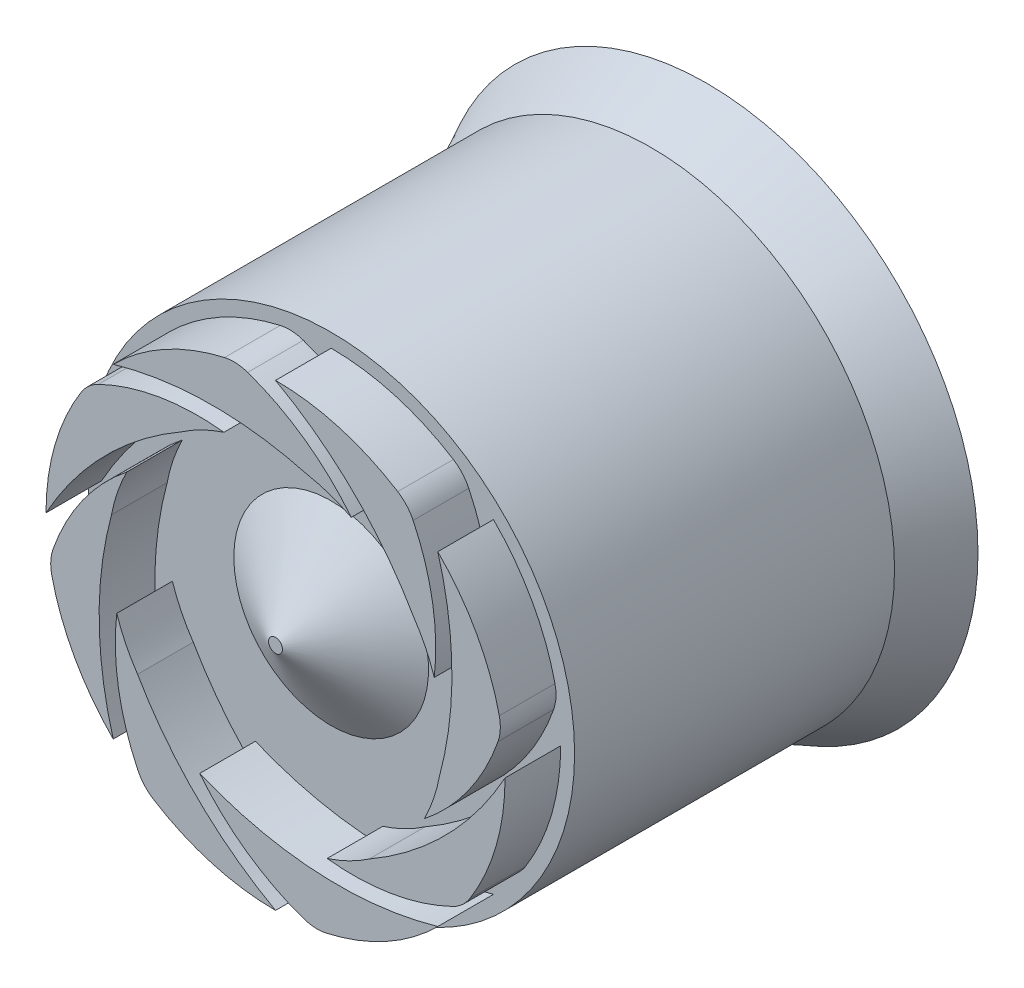
SolidWorks part; units mm, degrees
ref_plane "정면" through (0, 0, 0) normal (0, 0, 1) x (1, 0, 0)
ref_plane "윗면" through (0, 0, 0) normal (0, 1, 0) x (1, 0, 0)
ref_plane "우측면" through (0, 0, 0) normal (1, 0, 0) x (0, 0, -1)
sketch "스케치21" plane through (0, -5.7, 0) normal (0, 0, 1) x (-1, 0, 0)
  circle A0 centre (0, -5.7) radius 1.75
  dimension "3.6" = 3.5
extrude "보스-돌출8" add sketch "스케치21" along normal blind 0.3
ref_plane "평면1" through (0, 0, 0.1) normal (0, 0, 1) x (-1, 0, 0)
sketch "스케치22" plane through (0, 0, 0.3) normal (0, 0, 1) x (-1, 0, 0)
  circle A0 centre (0, 0) radius 0.7
  dimension "D1" = 1.4
extrude "컷-돌출4" cut sketch "스케치22" against normal blind 0.3
sketch "스케치23" plane through (0, 0, 0) normal (0, 1, 0) x (1, 0, 0)
  line L1 (1.75, 0) -> (-1.75, 0) construction
  line L2 (0, 0) -> (0.7, 0)
  line L3 (0.7, 0) -> (0.7, -0.3)
  line L4 (0.7, -0.3) -> (0.05, -0.7)
  line L5 (0.7, 0) -> (0, -0.4308)
  line L6 (0.05, -0.7) -> (0, -0.7)
  line L7 (0, -0.7) -> (0, -0.4308)
  dimension "D1" = 0.05
  dimension "D2" = 0.7
revolve "회전4" add sketch "스케치23" angle 360 about L7
sketch "스케치24" plane through (0, 0, 0) normal (0, 0, 1) x (1, 0, 0)
  circle A0 centre (0, 0) radius 1.65
  circle A2 centre (0, 0) radius 1.75 construction
  circle A3 centre (0, 0) radius 1.75
  dimension "D1" = 0.1
extrude "보스-돌출9" add sketch "스케치24" against normal blind 2
sketch "스케치33" plane through (0, 0, 0.3) normal (0, 0, 1) x (1, 0, 0)
  circle A0 centre (0, 0) radius 1.65
  circle A1 centre (0, 0) radius 1.75 construction
  arc A2 (0, 1.65) -> (0.8786, 1.3966) centre (0, 0) cw
  arc A3 (0.9893, 1.2726) -> (1.1412, 0.3709) centre (-0.4981, 0.5583) cw
  arc A4 (1.1412, 0.3709) -> (0, 1.65) centre (-1.2483, -0.6125) ccw
  circle A5 centre (0, 0) radius 1.2
  arc A6 (0.8786, 1.3966) -> (0.9893, 1.2726) centre (0.7188, 1.1427) cw
  arc A7 (1.1667, 1.1667) -> (1.6088, 0.3663) centre (0, 0) cw
  arc A8 (1.6088, 0.3663) -> (1.5994, 0.2003) centre (1.3163, 0.2997) cw
  arc A9 (1.5994, 0.2003) -> (1.0693, -0.5447) centre (0.0425, 0.747) cw
  arc A10 (1.0693, -0.5447) -> (1.1667, 1.1667) centre (-1.3158, 0.4496) ccw
  arc A11 (1.65, 0) -> (1.3966, -0.8786) centre (0, 0) cw
  arc A12 (1.3966, -0.8786) -> (1.2726, -0.9893) centre (1.1427, -0.7188) cw
  arc A13 (1.2726, -0.9893) -> (0.3709, -1.1412) centre (0.5583, 0.4981) cw
  arc A14 (0.3709, -1.1412) -> (1.65, 0) centre (-0.6125, 1.2483) ccw
  arc A15 (1.1667, -1.1667) -> (0.3663, -1.6088) centre (0, 0) cw
  arc A16 (0.3663, -1.6088) -> (0.2003, -1.5994) centre (0.2997, -1.3163) cw
  arc A17 (0.2003, -1.5994) -> (-0.5447, -1.0693) centre (0.747, -0.0425) cw
  arc A18 (-0.5447, -1.0693) -> (1.1667, -1.1667) centre (0.4496, 1.3158) ccw
  arc A19 (0, -1.65) -> (-0.8786, -1.3966) centre (0, 0) cw
  arc A20 (-0.8786, -1.3966) -> (-0.9893, -1.2726) centre (-0.7188, -1.1427) cw
  arc A21 (-0.9893, -1.2726) -> (-1.1412, -0.3709) centre (0.4981, -0.5583) cw
  arc A22 (-1.1412, -0.3709) -> (0, -1.65) centre (1.2483, 0.6125) ccw
  arc A23 (-1.1667, -1.1667) -> (-1.6088, -0.3663) centre (0, 0) cw
  arc A24 (-1.6088, -0.3663) -> (-1.5994, -0.2003) centre (-1.3163, -0.2997) cw
  arc A25 (-1.5994, -0.2003) -> (-1.0693, 0.5447) centre (-0.0425, -0.747) cw
  arc A26 (-1.0693, 0.5447) -> (-1.1667, -1.1667) centre (1.3158, -0.4496) ccw
  arc A27 (-1.65, 0) -> (-1.3966, 0.8786) centre (0, 0) cw
  arc A28 (-1.3966, 0.8786) -> (-1.2726, 0.9893) centre (-1.1427, 0.7188) cw
  arc A29 (-1.2726, 0.9893) -> (-0.3709, 1.1412) centre (-0.5583, -0.4981) cw
  arc A30 (-0.3709, 1.1412) -> (-1.65, 0) centre (0.6125, -1.2483) ccw
  arc A31 (-1.1667, 1.1667) -> (-0.3663, 1.6088) centre (0, 0) cw
  arc A32 (-0.3663, 1.6088) -> (-0.2003, 1.5994) centre (-0.2997, 1.3163) cw
  arc A33 (-0.2003, 1.5994) -> (0.5447, 1.0693) centre (-0.747, 0.0425) cw
  arc A34 (0.5447, 1.0693) -> (-1.1667, 1.1667) centre (-0.4496, -1.3158) ccw
  point P14 (0.9501, 1.349)
  point P66 (0, 0)
  dimension "D1" = 0.1
  dimension "D2" = 2.4
  dimension "D3" = 0.3
  dimension "D5" = 0.1663
  dimension "D4" = 2.584
  dimension "D6" = 8
extrude "보스-돌출10" add sketch "스케치33" along normal blind 0.4 contours A34 A5 A33 A32 A0 | A6 A0 A4 A5 A3 | A10 A5 A9 A8 A0 | A14 A5 A13 A12 A0 | A22 A5 A21 A20 A0 | A26 A5 A25 A24 A0 | A30 A5 A29 A28 A0 | A15 A16 A17 A18
sketch "스케치36" plane through (0, 0, 0) normal (0, 1, 0) x (1, 0, 0)
  line L0 (1.75, 2) -> (1.95, 2.4)
  line L1 (1.65, 2) -> (1.85, 2.4)
  line L2 (1.95, 2.4) -> (1.85, 2.4)
  line L3 (1.75, 2) -> (1.65, 2)
  line L4 (0, 0) -> (0, 0.6856) construction
  dimension "D1" = 0.2
  dimension "D2" = 0.4
revolve "회전5" add sketch "스케치36" angle 360 about L4
